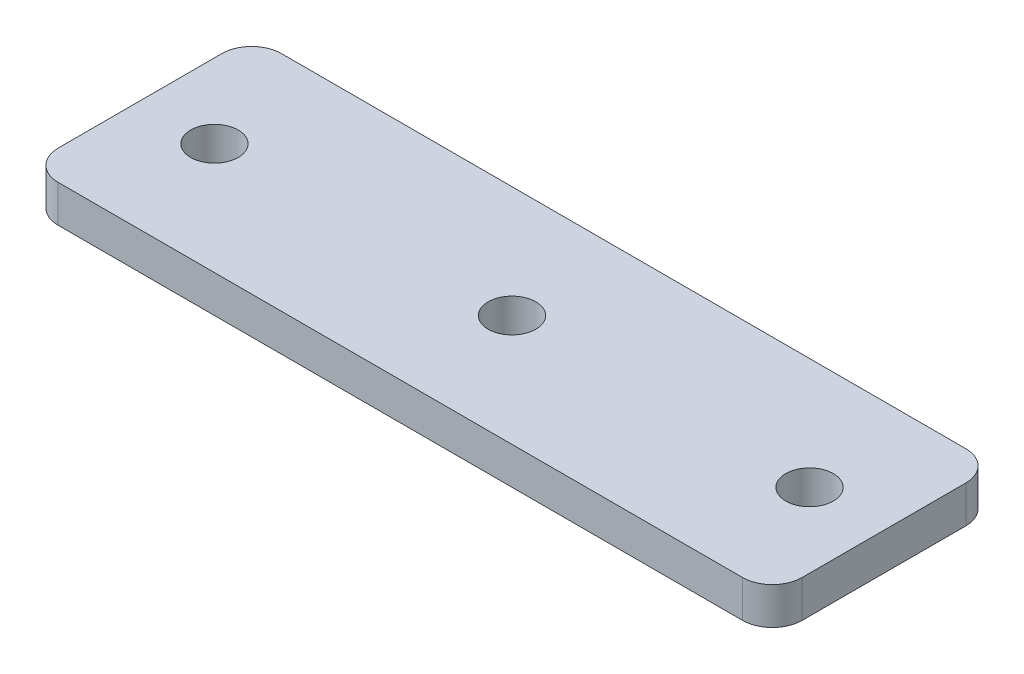
SolidWorks part; units mm, degrees
material "ABS"
ref_plane "前视基准面" through (0, 0, 0) normal (0, 0, 1) x (1, 0, 0)
ref_plane "上视基准面" through (0, 0, 0) normal (0, 1, 0) x (1, 0, 0)
ref_plane "右视基准面" through (0, 0, 0) normal (1, 0, 0) x (0, 0, -1)
other "Configuration Table"
sketch "草图1" plane through (0, 0, 0) normal (0, 1, 0) x (1, 0, 0)
  line L1 (-25, -7.5) -> (25, -7.5)
  line L2 (-25, -7.5) -> (-25, 7.5)
  line L3 (-25, 7.5) -> (25, 7.5)
  line L4 (25, -7.5) -> (25, 7.5)
  line L5 (-25, -7.5) -> (25, 7.5) construction
  line L6 (-25, 7.5) -> (25, -7.5) construction
  point P0 (0, 0)
  dimension "D1" = 15
  dimension "D2" = 50
extrude "凸台-拉伸1" add sketch "草图1" along normal blind 2.5
sketch "草图2" plane through (0, 2.5, 0) normal (0, 1, 0) x (1, 0, 0)
  line L0 (-25, 0) -> (25, 0) construction
  line L1 (-25, 7.5) -> (-25, -7.5) construction
  line L2 (25, -7.5) -> (25, 7.5) construction
  circle A0 centre (0, 0) radius 1.6
  circle A1 centre (-20, 0) radius 1.6
  circle A2 centre (20, 0) radius 1.6
  dimension "D1" = 3.2
  dimension "D2" = 3.2
  dimension "D3" = 3.2
  dimension "D4" = 20
  dimension "D5" = 20
extrude "切除-拉伸1" cut sketch "草图2" against normal through all
fillet "圆角1" radius 2 4 edges at (25, 1.25, -7.5) (25, 1.25, 7.5) (-25, 1.25, -7.5) (-25, 1.25, 7.5)
